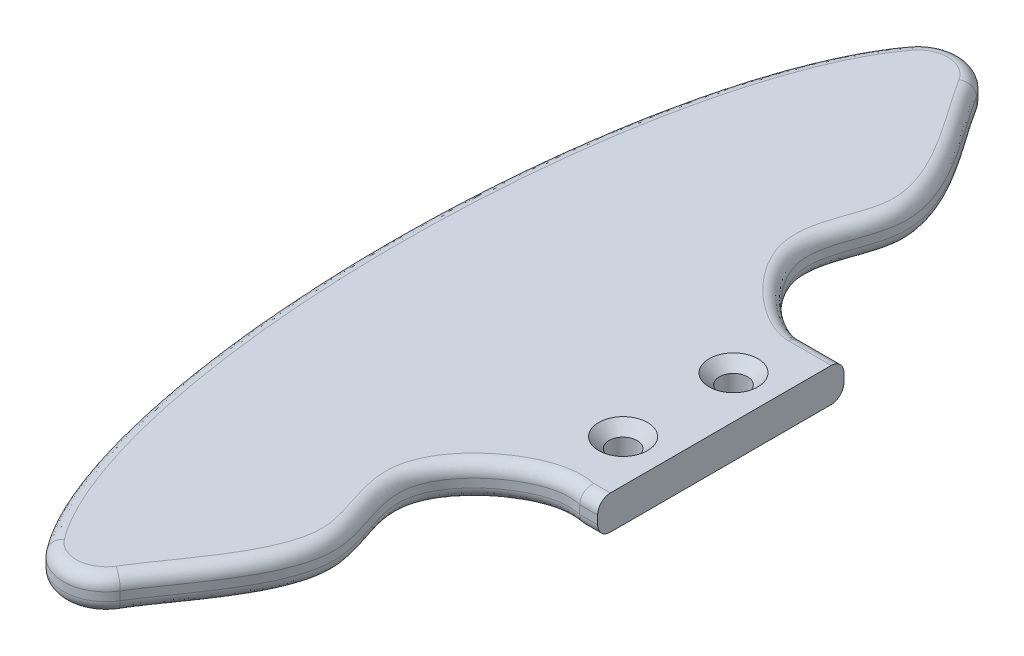
SolidWorks part; units mm, degrees
ref_plane "Ebene vorne" through (0, 0, 0) normal (0, 0, 1) x (1, 0, 0)
ref_plane "Ebene oben" through (0, 0, 0) normal (0, 1, 0) x (1, 0, 0)
ref_plane "Ebene rechts" through (0, 0, 0) normal (1, 0, 0) x (0, 0, -1)
sketch "Sketch1" plane through (0, 0, 0) normal (0, 1, 0) x (1, 0, 0)
  line L0 (19.5662, 0) -> (21.8809, 0) construction
  line L1 (16.8809, -14.5) -> (21.8809, -14.5)
  line L3 (16.8809, 14.5) -> (21.8809, 14.5)
  line L4 (21.8809, -14.5) -> (21.8809, 14.5)
  line L5 (17.5, 0) -> (9.7386, 0) construction
  ellipse E0 centre (0, 0) end of major axis (0, -55) minor radius 17.5 (16.8809, 14.5) -> (16.8809, -14.5) ccw
  dimension "D1" = 110
  dimension "D2" = 35
  dimension "D3" = 29
  dimension "D4" = 5
extrude "Boss-Extrude1" add sketch "Sketch1" along normal blind 4
sketch "Sketch2" plane through (0, 4, 0) normal (0, 1, 0) x (1, 0, 0)
  line L0 (16.8809, -14.5) -> (21.8809, -14.5) construction
  line L1 (21.8809, 14.5) -> (7.8809, 14.5)
  line L2 (21.8809, 14.5) -> (21.8809, -14.5)
  line L3 (21.8809, -14.5) -> (7.8809, -14.5)
  line L4 (7.8809, 14.5) -> (7.8809, -14.5)
  dimension "D1" = 14
extrude "Spacer" [suppressed] add sketch "Sketch2" along normal blind 5
sketch "Sketch4" [suppressed] plane through (0, 0, -14.5) normal (0, 0, -1) x (-1, 0, 0)
  line L0 (-25.2924, 9) -> (-39.2924, 3.9044)
  line L2 (-39.2924, 3.9044) -> (-39.2924, 9)
  line L3 (-39.2924, 9) -> (-25.2924, 9)
  dimension "D1" = 70
extrude "Angle" [suppressed] cut sketch "Sketch4" against normal up to surface (29 mm away)
sketch "Sketch6" [suppressed] plane through (5.8512, 16.076, 0) normal (0.342, 0.9397, 0) x (0.9397, -0.342, 0)
  line L0 (28.0874, 6.5) -> (28.0874, -6.5) construction
  line L1 (35.5874, -14.5) -> (35.5874, 14.5) construction
  line L2 (35.5874, 0) -> (20.6889, 0) construction
  line L3 (20.6889, 14.5) -> (20.6889, -14.5) construction
  line L4 (28.0874, 0) -> (51.5252, 0) construction
  circle A0 centre (28.0874, 6.5) radius 1.65
  circle A1 centre (28.0874, -6.5) radius 1.65
  dimension "D1" = 3.3
  dimension "D2" = 13
  dimension "D3" = 7.5
extrude "Cut-Extrude1" [suppressed] cut sketch "Sketch6" against normal through all
sketch "Sketch7" plane through (0, 4, 0) normal (0, 1, 0) x (1, 0, 0)
  line L0 (0, 55) -> (0, 12.0004) construction
  line L1 (-17.5, 0) -> (-3.5208, 0) construction
  line L2 (21.8809, 14.5) -> (16.8809, 14.5) construction
  line L3 (0, -55) -> (0, -15.7144) construction
  line L4 (16.8809, -14.5) -> (21.8809, -14.5) construction
  ellipse E0 centre (0, 0) end of major axis (0, -55) minor radius 17.5 (16.8809, 14.5) -> (16.8809, -14.5) ccw construction
  spline S0 degree 3 poles (62.2162, 43.7631) (14.9727, 40.778) (23.6962, 6.6255) (4.3063, 22.6804) (15.579, 37.0989) (-21.5373, 68.377) (62.2162, 43.7631) (14.9727, 40.778) (23.6962, 6.6255) knots -0.653805 -0.468518 -0.148074 0 0.169799 0.265053 0.346195 0.531482 0.851926 1 1.169799 1.265053 1.346195 only from (23.1423, 35.5) to (23.1423, 35.5)
  spline S1 degree 3 poles (30.2433, -31.2206) (23.5519, -6.7127) (4.694, -22.3493) (15.2883, -37.4155) (-20.6636, -66.6551) (50.2912, -53.3792) (30.2433, -31.2206) (23.5519, -6.7127) (4.694, -22.3493) knots -0.629722 -0.301663 -0.219893 0 0.097518 0.180588 0.370278 0.698337 0.780107 1 1.097518 1.180588 1.370278 only from (16.8809, -14.5) to (16.8809, -14.5)
  dimension "D3" = 20
  dimension "D1" = 10
  dimension "D2" = 8
  dimension "D4" = 40
  dimension "D5" = 21
  dimension "D6" = 30
  dimension "D7" = 21
  dimension "D8" = 32
  dimension "D9" = 40
  dimension "D10" = 30
  dimension "D11" = 32
  dimension "D12" = 10
  dimension "D13" = 8
  dimension "D14" = 20
extrude "Cut-Extrude3" cut sketch "Sketch7" against normal blind 10
fillet "Fillet1" radius 5 5 edges at (-17.5, 0, 0) (-17.5, 4, 0) (0, 2, -55)
fillet "Fillet2" radius 5 1 edges at (0, 2, 55)
fillet "Fillet4" radius 1.5 7 edges at (19.3809, 4, -14.5) (20.8282, 4, 14.5) (-17.5, 4, -0.1004) (-2.4565, 4, -52.7957) (-2.4843, 4, 52.7379)
fillet "Fillet5" radius 1.5 7 edges at (20.8282, 0, 14.5) (-17.5, 0, -0.1004) (-2.4565, 0, -52.7957) (-2.4843, 0, 52.7379) (19.3809, 0, -14.5)
sketch "Sketch8" plane through (0, 4, 0) normal (0, 1, 0) x (1, 0, 0)
  line L0 (21.8809, 0) -> (10.7021, 0) construction
  line L1 (21.8809, -13) -> (21.8809, 13) construction
  line L2 (16.8809, -6.5) -> (16.8809, 6.5) construction
  line L3 (16.8809, 0) -> (25.6639, 0) construction
  circle A0 centre (16.8809, -6.5) radius 1.65
  circle A1 centre (16.8809, 6.5) radius 1.65
  dimension "D1" = 3.3
  dimension "D2" = 5
  dimension "D3" = 13
extrude "M3 Screws no Angle" cut sketch "Sketch8" against normal through all
sketch "Sketch9" plane through (0, 4, 0) normal (0, 1, 0) x (1, 0, 0)
  circle A0 centre (16.8809, 6.5) radius 2.875
  circle A1 centre (16.8809, -6.5) radius 2.875
  dimension "D1" = 5.75
extrude "Cut-Extrude5" cut sketch "Sketch9" against normal blind 10 draft 45
